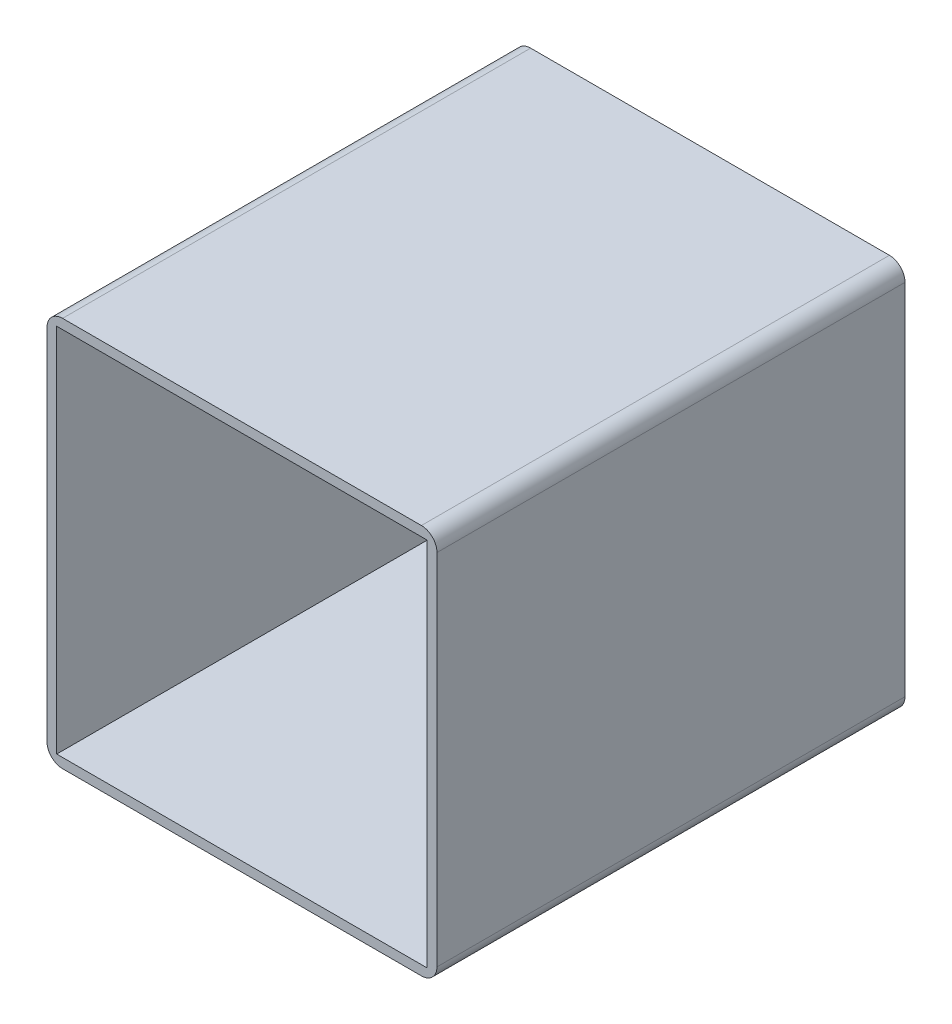
SolidWorks part; units mm, degrees
ref_plane "Front" through (0, 0, 0) normal (0, 0, 1) x (1, 0, 0)
ref_plane "Top" through (0, 0, 0) normal (0, 1, 0) x (1, 0, 0)
ref_plane "Right" through (0, 0, 0) normal (1, 0, 0) x (0, 0, -1)
sketch "Sketch1" plane through (0, 0, 0) normal (0, 0, 1) x (1, 0, 0)
  line L1 (-31.75, -31.75) -> (31.75, -31.75)
  line L2 (-31.75, -31.75) -> (-31.75, 31.75)
  line L3 (-31.75, 31.75) -> (31.75, 31.75)
  line L4 (31.75, -31.75) -> (31.75, 31.75)
  line L5 (-31.75, -31.75) -> (31.75, 31.75) construction
  line L6 (-31.75, 31.75) -> (31.75, -31.75) construction
  point P0 (0, 0)
  dimension "D1" = 63.5
  dimension "D2" = 63.5
extrude "Boss-Extrude1" add sketch "Sketch1" along normal blind 76.2
sketch "Sketch2" plane through (0, 0, 76.2) normal (0, 0, 1) x (1, 0, 0)
  line L8 (30.1625, -30.1625) -> (30.1625, 30.1625)
  line L9 (30.1625, 30.1625) -> (-30.1625, 30.1625)
  line L10 (-30.1625, 30.1625) -> (-30.1625, -30.1625)
  line L11 (-30.1625, -30.1625) -> (30.1625, -30.1625)
  line L12 (30.1625, -30.1625) -> (30.1625, 30.1625)
  line L13 (30.1625, 30.1625) -> (-30.1625, 30.1625)
  line L14 (-30.1625, 30.1625) -> (-30.1625, -30.1625)
  line L15 (-30.1625, -30.1625) -> (30.1625, -30.1625)
  dimension "D1" = 1.5875
extrude "Cut-Extrude1" cut sketch "Sketch2" against normal offset from surface (75.4 mm away) 0.8 up to face at (0, 0, 0)
fillet "Fillet1" radius 2.54 4 edges at (-31.75, -31.75, 38.1) (31.75, -31.75, 38.1) (31.75, 31.75, 38.1) (-31.75, 31.75, 38.1)
sketch "Sketch3" plane through (0, 0, 0) normal (0, 0, -1) x (-1, 0, 0)
  line L0 (0, -31.75) -> (0, 31.75) construction
  line L1 (29.21, -31.75) -> (-29.21, -31.75) construction
  line L2 (-29.21, 31.75) -> (29.21, 31.75) construction
  line L3 (0, 31.75) -> (31.75, 0) construction
  line L4 (31.75, 29.21) -> (31.75, -29.21) construction
  line L5 (31.75, 0) -> (-31.75, 0) construction
  line L6 (-31.75, -29.21) -> (-31.75, 29.21) construction
  circle A0 centre (0, 19.05) radius 3.175
  circle A1 centre (0, -19.05) radius 3.175
  circle A2 centre (0, 0) radius 3.175
  circle A3 centre (19.05, 0) radius 3.175
  circle A4 centre (-19.05, 0) radius 3.175
  dimension "D1" = 6.35
  dimension "D2" = 6.35
  dimension "D3" = 6.35
  dimension "D4" = 6.35
  dimension "D5" = 6.35
  dimension "D6" = 19.05
  dimension "D7" = 19.05
  dimension "D8" = 19.05
  dimension "D9" = 19.05
extrude "Cut-Extrude2" cut sketch "Sketch3" against normal through all
sketch "Sketch4" plane through (0, 0, 0) normal (0, 0, -1) x (-1, 0, 0)
  line L0 (-31.75, -19.05) -> (31.75, -19.05) construction
  line L1 (-31.75, -29.21) -> (-31.75, 29.21) construction
  line L2 (31.75, 29.21) -> (31.75, -29.21) construction
  line L3 (0, 0) -> (0, -19.05) construction
  circle A0 centre (-15.875, -19.05) radius 4.064
  circle A1 centre (15.875, -19.05) radius 4.064
  dimension "D1" = 8.128
  dimension "D2" = 8.128
  dimension "D3" = 15.875
  dimension "D4" = 15.875
extrude "Cut-Extrude3" cut sketch "Sketch4" against normal through all
